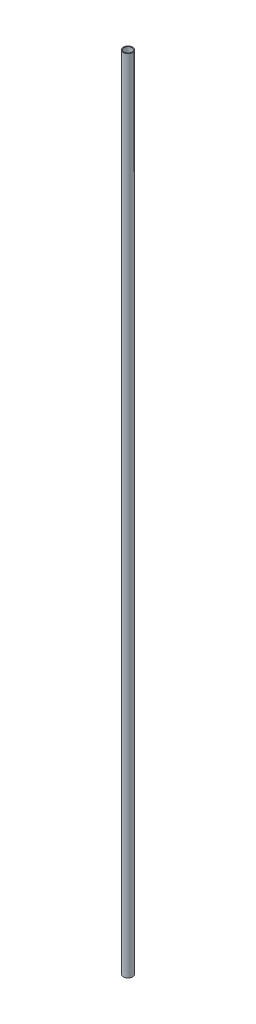
SolidWorks part; units mm, degrees
ref_plane "Front Plane" through (0, 0, 0) normal (0, 0, 1) x (1, 0, 0)
ref_plane "Top Plane" through (0, 0, 0) normal (0, 1, 0) x (1, 0, 0)
ref_plane "Right Plane" through (0, 0, 0) normal (1, 0, 0) x (0, 0, -1)
sketch "Sketch1" plane through (0, 0, 0) normal (0, 1, 0) x (1, 0, 0)
  circle A0 centre (0, 0) radius 2.35
  circle A1 centre (0, 0) radius 1.95
  dimension "D1" = 4.7
  dimension "D2" = 3.9
extrude "Extrude1" add sketch "Sketch1" along normal blind 400
